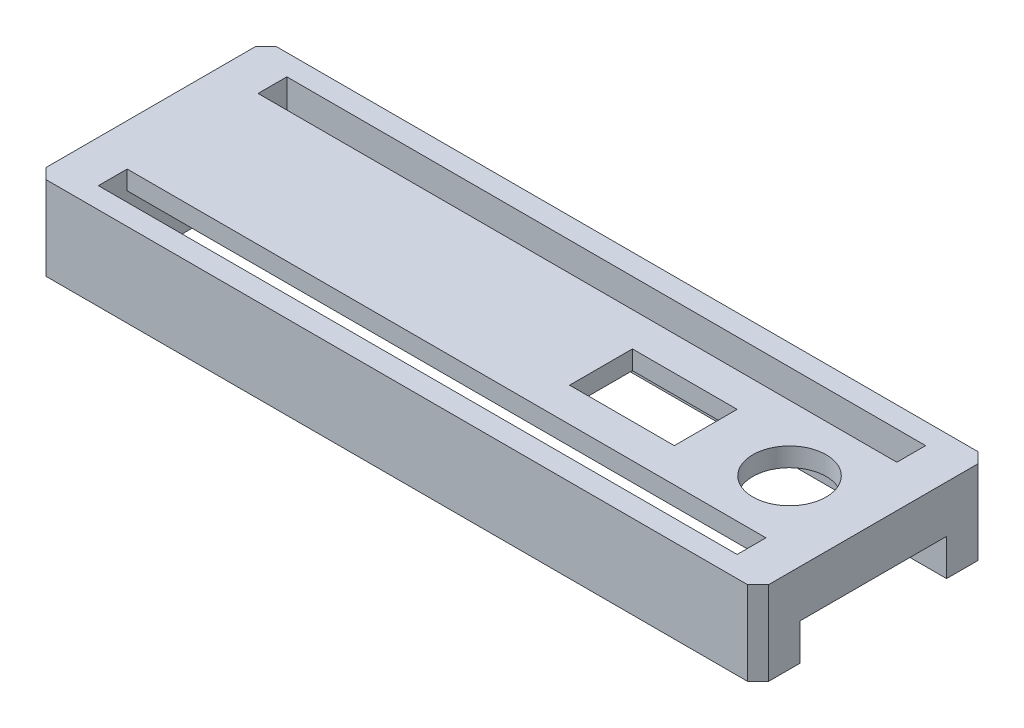
SolidWorks part; units mm, degrees
ref_plane "Front Plane" through (0, 0, 0) normal (0, 0, 1) x (1, 0, 0)
ref_plane "Top Plane" through (0, 0, 0) normal (0, 1, 0) x (1, 0, 0)
ref_plane "Right Plane" through (0, 0, 0) normal (1, 0, 0) x (0, 0, -1)
sketch "Sketch1" plane through (0, 0, 0) normal (0, 1, 0) x (1, 0, 0)
  line L0 (-35, 12) -> (35, 12)
  line L1 (-35, 0) -> (35, 0)
  line L2 (35, 0) -> (35, 12)
  line L3 (-35, 12) -> (-35, 0)
  point P4 (0, 0)
  dimension "D1" = 70
  dimension "D2" = 12
extrude "Boss-Extrude1" add sketch "Sketch1" along normal blind 1.8
sketch "Sketch2" plane through (0, 1.8, 0) normal (0, 1, 0) x (1, 0, 0)
  line L6 (-35, 15) -> (-35, -3)
  line L7 (-35, -3) -> (-31, -3)
  line L8 (-31, -3) -> (-31, 15)
  line L9 (-31, 15) -> (-35, 15)
  line L10 (35, 12) -> (-35, 12) construction
  dimension "D1" = 18
  dimension "D2" = 3
  dimension "D3" = 4
extrude "Boss-Extrude2" add sketch "Sketch2" against normal blind 8
sketch "Sketch3" plane through (0, 0, 0) normal (0, -1, 0) x (1, 0, 0)
  line L2 (30, -15) -> (35, -15)
  line L3 (35, -15) -> (35, 3)
  line L4 (35, 3) -> (30, 3)
  line L6 (30, 3) -> (30, -15)
  line L7 (-31, 0) -> (35, 0) construction
  line L8 (35, 0) -> (35, -12) construction
  dimension "D1" = 18
  dimension "D2" = 3
  dimension "D3" = 5
extrude "Boss-Extrude3" add sketch "Sketch3" along normal up to surface and the other way up to surface up to face at (-33, -6.2, -6) other way up to face at (-15.5, 1.8, -6)
sketch "Sketch4" plane through (0, -6.2, 0) normal (0, -1, 0) x (1, 0, 0)
  line L0 (30, 1) -> (35, 1)
  line L1 (30, 0) -> (30, -12) construction
  line L2 (35, 3) -> (35, -15) construction
  line L3 (35, 1) -> (35, -13)
  line L4 (35, -13) -> (30, -13)
  line L5 (30, -13) -> (30, 1)
  line L6 (30, 3) -> (35, 3) construction
  line L7 (35, -15) -> (30, -15) construction
  dimension "D1" = 2
  dimension "D2" = 2
extrude "Cut-Extrude1" cut sketch "Sketch4" against normal blind 3.5
sketch "Sketch5" plane through (0, 1.8, 0) normal (0, 1, 0) x (1, 0, 0)
  line L1 (-31, 12.25) -> (-31, -0.25)
  line L2 (30, 12) -> (30, 15) construction
  line L4 (30, -3) -> (30, 0) construction
  line L6 (30, 12.25) -> (30, -0.25)
  line L8 (-31, 12.25) -> (30, 12.25)
  line L9 (-31, 12) -> (-31, 15) construction
  line L11 (30, -0.25) -> (-31, -0.25)
  line L12 (-31, -3) -> (-31, 0) construction
  line L14 (35, -3) -> (35, 15) construction
  point P10 (35, 6)
  dimension "D1" = 6.25
  dimension "D2" = 12.5
extrude "Boss-Extrude4" add sketch "Sketch5" against normal up to surface (1.8 mm away) up to face at (-0.5, 0, -6)
sketch "Sketch7" plane through (0, 1.8, 0) normal (0, 1, 0) x (1, 0, 0)
  line L0 (-35, 15) -> (35, 15)
  line L1 (35, 15) -> (35, 17)
  line L2 (35, 17) -> (-35, 17)
  line L3 (-35, 17) -> (-35, 15)
  line L4 (-35, -3) -> (35, -3)
  line L5 (35, -3) -> (35, -5)
  line L6 (35, -5) -> (-35, -5)
  line L7 (-35, -5) -> (-35, -3)
  dimension "D1" = 2
  dimension "D2" = 2
extrude "Boss-Extrude5" add sketch "Sketch7" against normal up to surface (8 mm away) up to face at (32.5, -6.2, -14)
sketch "Sketch10" plane through (0, 1.8, 0) normal (0, 1, 0) x (1, 0, 0)
  line L0 (35, -5) -> (35, 17) construction
  line L1 (30, 12.25) -> (30, 15) construction
  circle A0 centre (26, 6) radius 3.5
  point P2 (0, 0)
  point P5 (35, 6)
  dimension "D1" = 7
  dimension "D2" = 4
extrude "Cut-Extrude2" cut sketch "Sketch10" against normal up to surface (1.8 mm away) up to face at (-0.5, 0, -6)
sketch "Sketch11" plane through (0, 1.8, 0) normal (0, 1, 0) x (1, 0, 0)
  line L0 (35, -5) -> (35, 17) construction
  line L1 (8, 3) -> (18, 3)
  line L2 (8, 3) -> (8, 9)
  line L3 (8, 9) -> (18, 9)
  line L4 (18, 3) -> (18, 9)
  line L5 (8, 3) -> (18, 9) construction
  line L6 (8, 9) -> (18, 3) construction
  circle A1 centre (26, 6) radius 3.5 construction
  point P0 (13, 6)
  point P5 (0, 0)
  point P8 (35, 6)
  dimension "D1" = 10
  dimension "D2" = 6
  dimension "D3" = 8
extrude "Cut-Extrude3" cut sketch "Sketch11" against normal up to surface (1.8 mm away) up to face at (26, 0, -2.5)
sketch "Sketch12" plane through (0, 1.8, 0) normal (0, 1, 0) x (1, 0, 0)
  line L0 (34, 17) -> (34, -5)
  line L1 (35, 17) -> (-35, 17) construction
  line L2 (-35, -5) -> (35, -5) construction
  line L3 (34, -5) -> (35, -5)
  line L4 (35, -5) -> (35, 17)
  line L5 (35, 17) -> (34, 17)
  dimension "D1" = 1
extrude "Cut-Extrude4" cut sketch "Sketch12" against normal up to surface (8 mm away)
chamfer "Chamfer1" distance 1 angle 45 4 edges at (-35, -2.2, -17) (-35, -2.2, 5) (34, -2.2, 5) (34, -2.2, -17)
